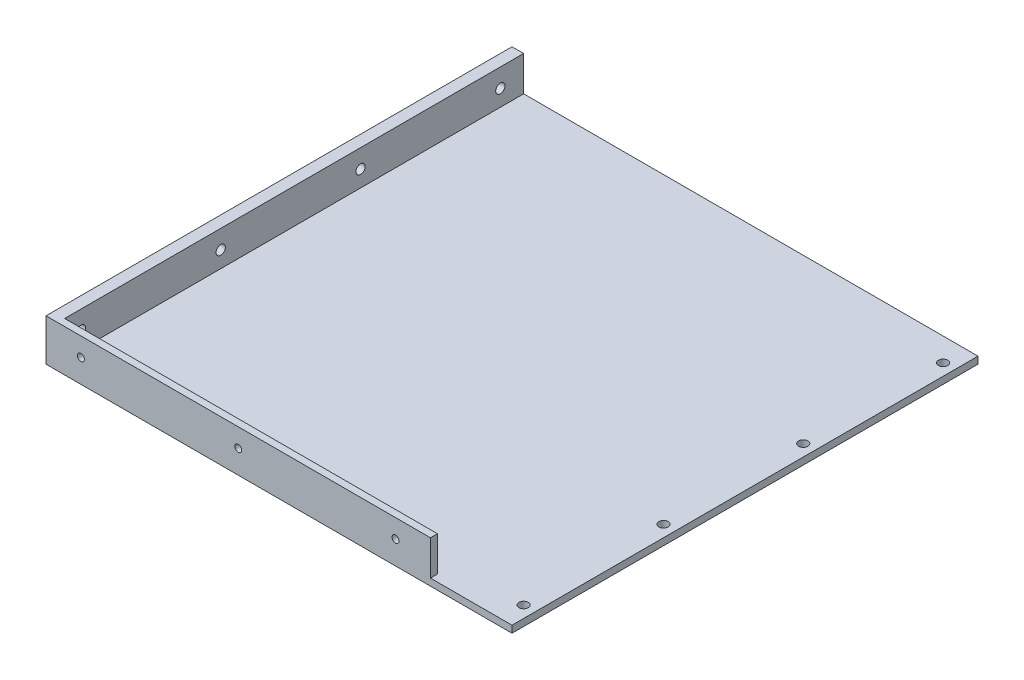
SolidWorks part; units mm, degrees
ref_plane "Front Plane" through (0, 0, 0) normal (0, 0, 1) x (1, 0, 0)
ref_plane "Top Plane" through (0, 0, 0) normal (0, 1, 0) x (1, 0, 0)
ref_plane "Right Plane" through (0, 0, 0) normal (1, 0, 0) x (0, 0, -1)
sketch "Sketch1" plane through (0, 0, 0) normal (0, 1, 0) x (1, 0, 0)
  line L1 (-100, -100) -> (100, -100)
  line L2 (-100, -100) -> (-100, 100)
  line L3 (-100, 100) -> (100, 100)
  line L4 (100, -100) -> (100, 100)
  line L5 (-100, -100) -> (100, 100) construction
  line L6 (-100, 100) -> (100, -100) construction
  point P0 (0, 0)
  dimension "D1" = 200
  dimension "D2" = 200
extrude "Boss-Extrude1" add sketch "Sketch1" along normal blind 3
sketch "Sketch2" plane through (0, 3, 0) normal (0, 1, 0) x (1, 0, 0)
  line L0 (-100, -100) -> (100, -100) construction
  line L1 (-100, 100) -> (-95, 100)
  line L2 (-100, 100) -> (-100, -100)
  line L3 (-100, -100) -> (-95, -100)
  line L4 (-95, 100) -> (-95, -100)
  dimension "D1" = 5
extrude "Boss-Extrude2" add sketch "Sketch2" along normal blind 15
sketch "Sketch3" plane through (-100, 0, 0) normal (-1, 0, 0) x (0, 0, 1)
  line L0 (-100, 0) -> (100, 0) construction
  line L1 (100, 18) -> (100, 0) construction
  circle A0 centre (90, 10) radius 2
  dimension "D1" = 4
  dimension "D2" = 10
  dimension "D3" = 10
extrude "Cut-Extrude1" cut sketch "Sketch3" against normal up to next
pattern_linear "LPattern1" count 4 spacing 60 along (0, 0, -1) of "Cut-Extrude1"
sketch "Sketch4" plane through (0, 3, 0) normal (0, 1, 0) x (1, 0, 0)
  line L0 (100, -100) -> (100, 100) construction
  line L1 (100, 100) -> (-95, 100) construction
  circle A0 centre (95, 90) radius 2
  dimension "D1" = 4
  dimension "D2" = 5
  dimension "D3" = 10
extrude "Cut-Extrude2" cut sketch "Sketch4" against normal up to next
pattern_linear "LPattern2" count 4 spacing 60 along (0, 0, 1) of "Cut-Extrude2"
sketch "Sketch5" plane through (0, 3, 0) normal (0, 1, 0) x (1, 0, 0)
  line L1 (-95, -100) -> (65, -100)
  line L2 (-95, -100) -> (-95, -97)
  line L3 (-95, -97) -> (65, -97)
  line L4 (65, -100) -> (65, -97)
  dimension "D1" = 160
  dimension "D2" = 3
extrude "Boss-Extrude3" add sketch "Sketch5" along normal blind 15
sketch "Sketch6" plane through (0, 0, 100) normal (0, 0, 1) x (1, 0, 0)
  line L0 (-100, 18) -> (-100, 0) construction
  line L1 (65, 18) -> (65, 3) construction
  line L2 (-100, 0) -> (100, 0) construction
  circle A0 centre (-85, 10) radius 1.5
  circle A1 centre (-17.5, 10) radius 1.5
  circle A2 centre (50, 10) radius 1.5
  point P10 (0, 0)
  point P13 (0, 0)
  dimension "D1" = 3
  dimension "D2" = 3
  dimension "D3" = 3
  dimension "D4" = 15
  dimension "D5" = 15
  dimension "D6" = 67.5
  dimension "D7" = 10
extrude "Cut-Extrude3" cut sketch "Sketch6" against normal up to next
